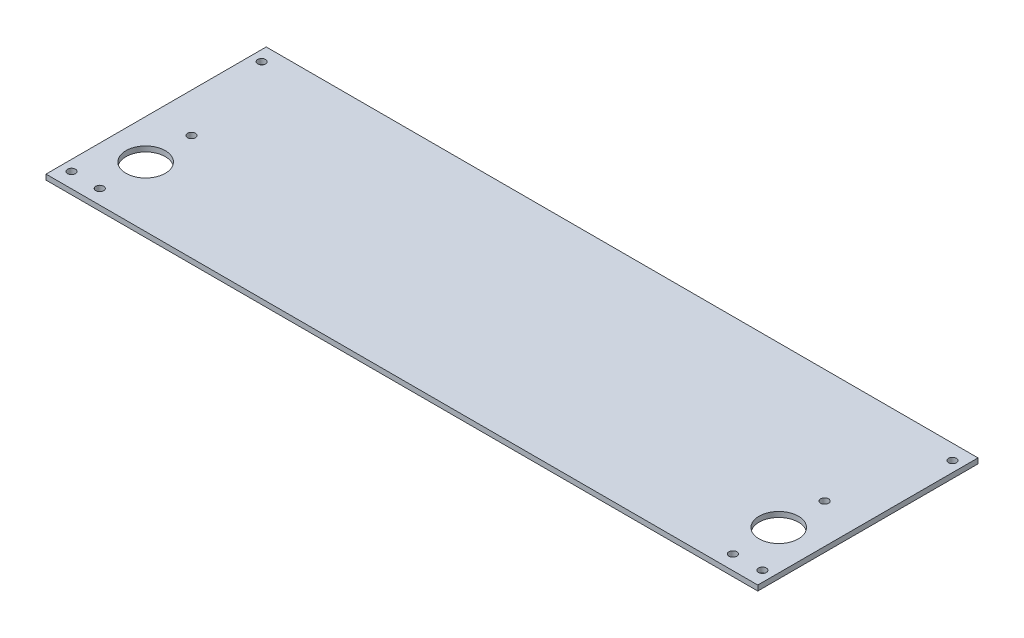
SolidWorks part; units mm, degrees
ref_plane "Front Plane" through (0, 0, 0) normal (0, 0, 1) x (1, 0, 0)
ref_plane "Top Plane" through (0, 0, 0) normal (0, 1, 0) x (1, 0, 0)
ref_plane "Right Plane" through (0, 0, 0) normal (1, 0, 0) x (0, 0, -1)
sketch "Sketch1" plane through (0, 0, 0) normal (0, 1, 0) x (1, 0, 0)
  line L1 (0, 0) -> (271.5, 0)
  line L2 (0, 0) -> (0, 84)
  line L3 (0, 84) -> (271.5, 84)
  line L4 (271.5, 0) -> (271.5, 84)
  circle A0 centre (4, 5.75) radius 1.5
  circle A1 centre (4, 78.25) radius 1.5
  circle A2 centre (267.5, 5.75) radius 1.5
  circle A3 centre (267.5, 78.25) radius 1.5
  dimension "D3" = 5.75
  dimension "D4" = 3
  dimension "D6" = 3
  dimension "D13" = 3
  dimension "D14" = 3
  dimension "D1" = 271.5
  dimension "D2" = 84
  dimension "D5" = 4
  dimension "D7" = 5.75
  dimension "D8" = 4
  dimension "D9" = 4
  dimension "D10" = 5.75
  dimension "D11" = 4
  dimension "D12" = 5.75
extrude "Boss-Extrude1" add sketch "Sketch1" along normal blind 2
sketch "Sketch2" plane through (0, 2, 0) normal (0, 1, 0) x (1, 0, 0)
  line L0 (15, 40.5) -> (15, 5.5) construction
  line L1 (0, 0) -> (271.5, 0) construction
  line L2 (0, 84) -> (0, 0) construction
  line L3 (135.75, 84) -> (135.75, 0) construction
  line L4 (271.5, 84) -> (0, 84) construction
  line L5 (256.5, 40.5) -> (256.5, 5.5) construction
  circle A0 centre (15, 5.5) radius 1.5
  circle A1 centre (15, 40.5) radius 1.5
  circle A2 centre (15, 23) radius 7.5
  circle A3 centre (256.5, 23) radius 7.5
  circle A4 centre (256.5, 40.5) radius 1.5
  circle A5 centre (256.5, 5.5) radius 1.5
  dimension "D1" = 35
  dimension "D2" = 3
  dimension "D3" = 15
  dimension "D4" = 5.5
  dimension "D5" = 15
extrude "Cut-Extrude1" cut sketch "Sketch2" against normal blind 10
